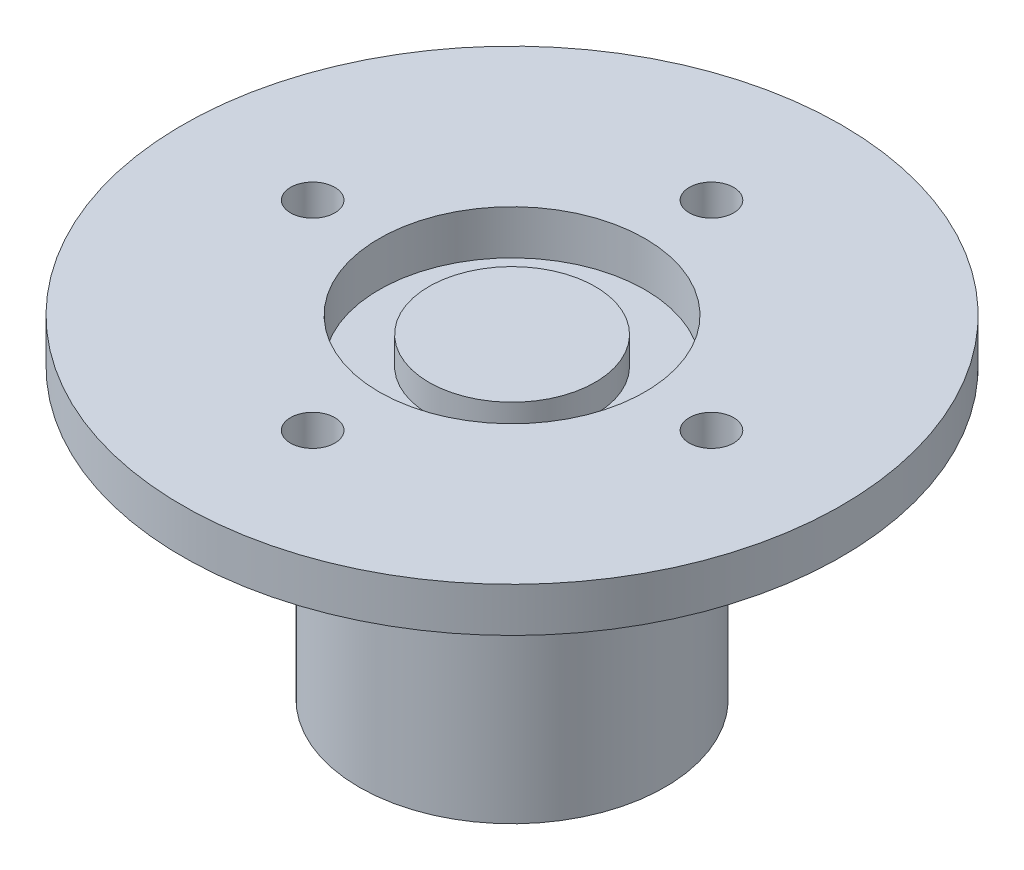
SolidWorks part; units mm, degrees
ref_plane "Front Plane" through (0, 0, 0) normal (0, 0, 1) x (1, 0, 0)
ref_plane "Top Plane" through (0, 0, 0) normal (0, 1, 0) x (1, 0, 0)
ref_plane "Right Plane" through (0, 0, 0) normal (1, 0, 0) x (0, 0, -1)
sketch "Sketch1" plane through (0, 0, 0) normal (0, 1, 0) x (1, 0, 0)
  circle A0 centre (0, 0) radius 7.5
  dimension "D1" = 15
extrude "Boss-Extrude1" add sketch "Sketch1" along normal blind 2.5
sketch "Sketch2" plane through (0, 0, 0) normal (0, -1, 0) x (1, 0, 0)
  circle A0 centre (0, 0) radius 12
  circle A1 centre (0, 0) radius 29.75
  dimension "D1" = 24
  dimension "D2" = 59.5
extrude "Boss-Extrude2" add sketch "Sketch2" against normal blind 4 separate body
sketch "Sketch3" plane through (0, 0, 0) normal (0, -1, 0) x (1, 0, 0)
  circle A0 centre (0, 0) radius 13.8
  dimension "D1" = 27.6
extrude "Boss-Extrude3" add sketch "Sketch3" along normal blind 26
sketch "Sketch4" plane through (0, -26, 0) normal (0, -1, 0) x (1, 0, 0)
  circle A0 centre (0, 0) radius 5
  dimension "D1" = 10
extrude "Cut-Extrude1" cut sketch "Sketch4" against normal offset from surface (25.5 mm away) 3 up to face at (0, 2.5, 7.5)
sketch "Sketch5" plane through (0, 4, 0) normal (0, 1, 0) x (1, 0, 0)
  line L0 (0, 0) -> (0, 18) construction
  circle A0 centre (0, 18) radius 2
  circle A1 centre (18, 0) radius 2
  circle A2 centre (0, -18) radius 2
  circle A3 centre (-18, 0) radius 2
  point P4 (-22.302, -7.9355)
  point P5 (0, 0)
  point P6 (0, 0)
  point P13 (0, 0)
  dimension "D1" = 4
  dimension "D2" = 18
  dimension "D3" = 4
extrude "Cut-Extrude2" cut sketch "Sketch5" against normal through all
